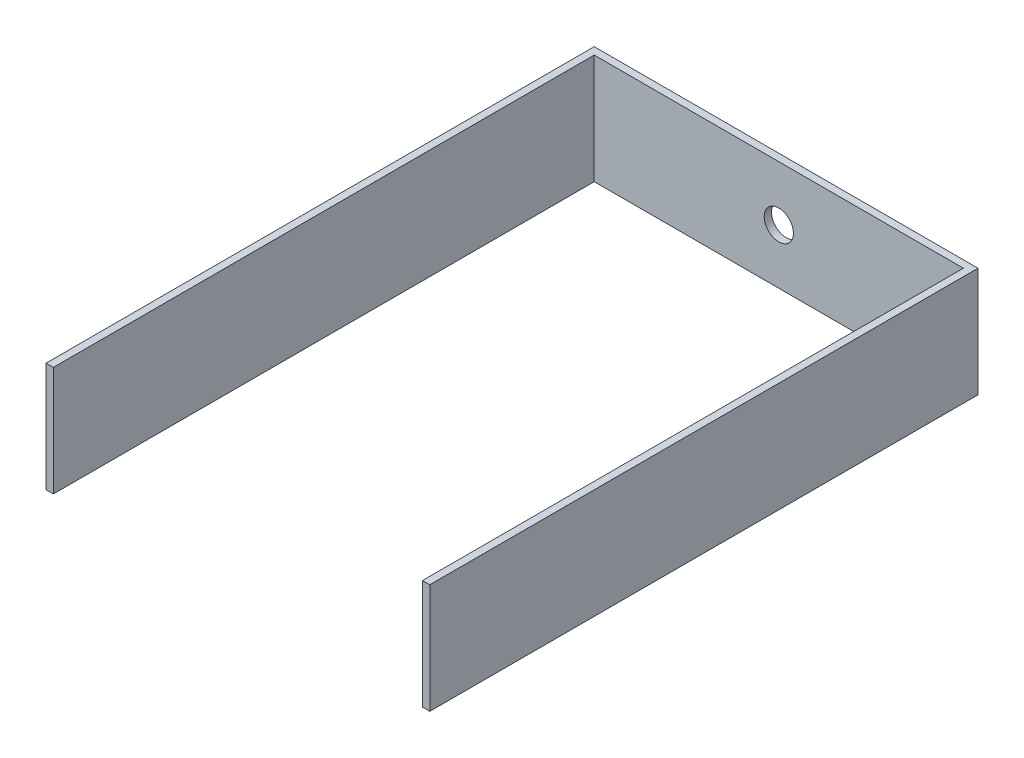
SolidWorks part; units mm, degrees
ref_plane "Front" through (0, 0, 0) normal (0, 0, 1) x (1, 0, 0)
ref_plane "Top" through (0, 0, 0) normal (0, 1, 0) x (1, 0, 0)
ref_plane "Right" through (0, 0, 0) normal (1, 0, 0) x (0, 0, -1)
sketch "Sketch1" plane through (0, 0, 0) normal (0, 1, 0) x (1, 0, 0)
  line L0 (50.5, -2) -> (50.5, -150)
  line L1 (-52.5, 0) -> (52.5, 0)
  line L2 (-52.5, 0) -> (-52.5, -150)
  line L4 (52.5, 0) -> (52.5, -150)
  line L5 (-50.5, -2) -> (50.5, -2)
  line L6 (-50.5, -2) -> (-50.5, -150)
  line L7 (-52.5, -150) -> (-50.5, -150)
  line L8 (52.5, -150) -> (50.5, -150)
  point P0 (0, 0)
  dimension "D1" = 105
  dimension "D2" = 150
  dimension "D4" = 52.5
  dimension "D5" = 150
  dimension "D6" = 0
  dimension "D3" = 2
extrude "Boss-Extrude1" add sketch "Sketch1" along normal mid plane 30 contours L2 L7 L6 L5 L0 L8 L4 L1
sketch "Sketch2" plane through (0, 0, 0) normal (0, 0, -1) x (-1, 0, 0)
  line L0 (52.5, 15) -> (-52.5, 15) construction
  circle A0 centre (0, 0) radius 4
  dimension "D3" = 8
  dimension "D1" = 15
  dimension "D2" = 0
extrude "Cut-Extrude1" cut sketch "Sketch2" against normal through all
sketch "Sketch3" plane through (0, 0, 0) normal (0, 0, -1) x (-1, 0, 0)
  line L0 (0, 0) -> (0, 50.681) construction
